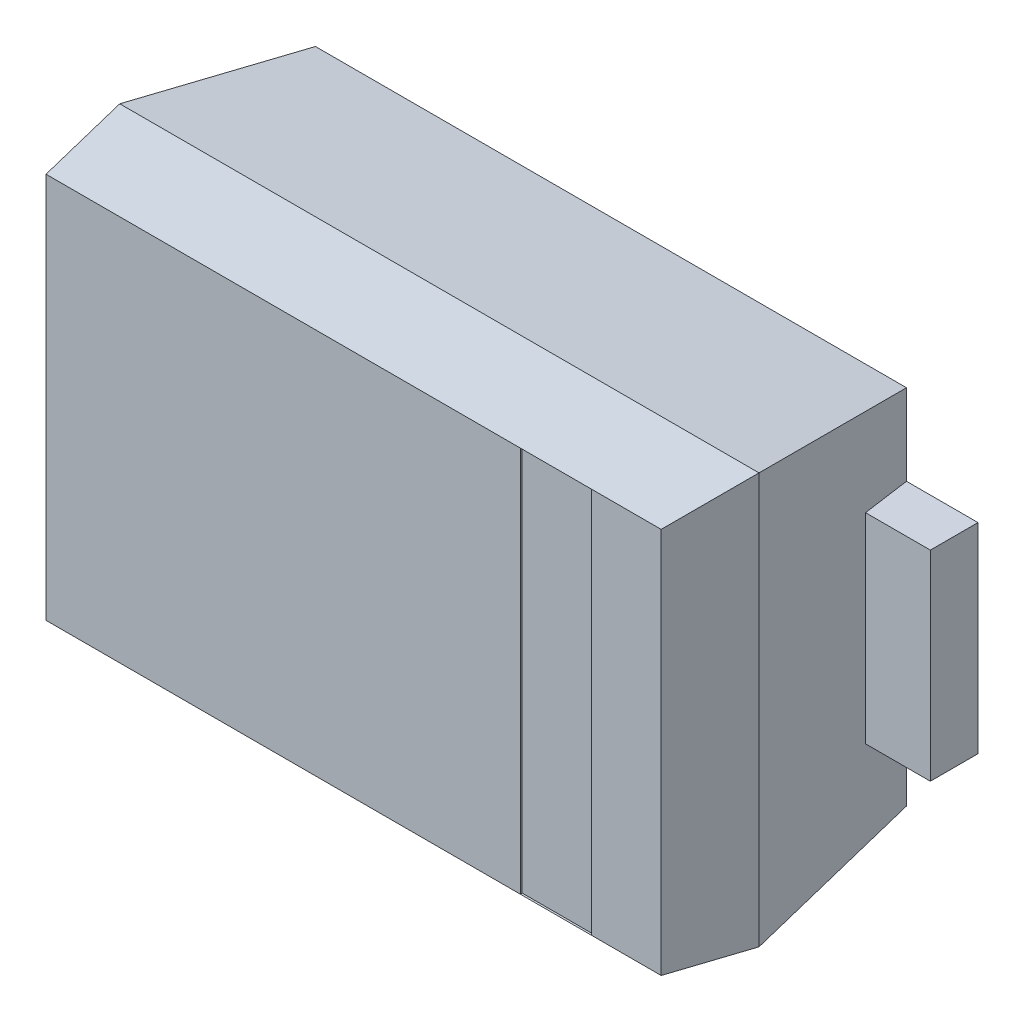
SolidWorks part; units mm, degrees
ref_plane "Alzado" through (0, 0, 0) normal (0, 0, 1) x (1, 0, 0)
ref_plane "Planta" through (0, 0, 0) normal (0, 1, 0) x (1, 0, 0)
ref_plane "Vista lateral" through (0, 0, 0) normal (1, 0, 0) x (0, 0, -1)
sketch "Croquis1" plane through (0, 0, 0) normal (0, 0, 1) x (1, 0, 0)
  line L1 (1.925, 0.525) -> (-1.925, 0.525)
  line L2 (1.925, 0.525) -> (1.925, -0.525)
  line L3 (1.925, -0.525) -> (-1.925, -0.525)
  line L4 (-1.925, 0.525) -> (-1.925, -0.525)
  line L5 (1.925, 0.525) -> (-1.925, -0.525) construction
  line L6 (1.925, -0.525) -> (-1.925, 0.525) construction
  point P0 (0, 0)
  dimension "D1" = 3.85
  dimension "D2" = 1.05
extrude "Saliente-Extruir1" add sketch "Croquis1" along normal blind 0.25
sketch "Croquis2" plane through (0, 0, 0) normal (0, 0, -1) x (-1, 0, 0)
  line L0 (0, 0.525) -> (0, -0.525) construction
  line L1 (-1.925, 0.525) -> (1.925, 0.525) construction
  line L2 (1.925, -0.525) -> (-1.925, -0.525) construction
  line L3 (0, 0) -> (-1.925, 0) construction
  line L4 (-1.925, -0.525) -> (-1.925, 0.525) construction
  line L6 (1.55, 0.95) -> (-1.55, 0.95)
  line L7 (1.55, 0.95) -> (1.55, -0.95)
  line L8 (1.55, -0.95) -> (-1.55, -0.95)
  line L9 (-1.55, 0.95) -> (-1.55, -0.95)
  line L10 (1.55, 0.95) -> (-1.55, -0.95) construction
  line L11 (1.55, -0.95) -> (-1.55, 0.95) construction
  dimension "D1" = 1.9
  dimension "D2" = 3.1
extrude "Saliente-Extruir2" add sketch "Croquis2" against normal blind 0.9 draft 8 draft outward yes
sketch "Croquis3" plane through (0, 0, 0.9) normal (0, 0, 1) x (1, 0, 0)
  line L1 (1.6765, 1.0765) -> (-1.6765, 1.0765)
  line L2 (1.6765, 1.0765) -> (1.6765, -1.0765)
  line L3 (1.6765, -1.0765) -> (-1.6765, -1.0765)
  line L4 (-1.6765, 1.0765) -> (-1.6765, -1.0765)
  line L5 (1.6765, 1.0765) -> (-1.6765, -1.0765) construction
  line L6 (1.6765, -1.0765) -> (-1.6765, 1.0765) construction
  point P0 (0, 0)
extrude "Saliente-Extruir3" add sketch "Croquis3" along normal blind 0.45 draft 8
sketch "Croquis4" plane through (0, 0, 1.35) normal (0, 0, 1) x (1, 0, 0)
  line L0 (1.6132, 1.0132) -> (-1.6132, 1.0132) construction
  line L1 (1.2466, 1.0132) -> (0.8743, 1.0132)
  line L2 (1.2466, 1.0132) -> (1.2466, -1.0132)
  line L3 (1.2466, -1.0132) -> (0.8743, -1.0132)
  line L4 (0.8743, 1.0132) -> (0.8743, -1.0132)
  line L5 (-1.6132, -1.0132) -> (1.6132, -1.0132) construction
extrude "Cortar-Extruir1" cut sketch "Croquis4" against normal blind 0.01
